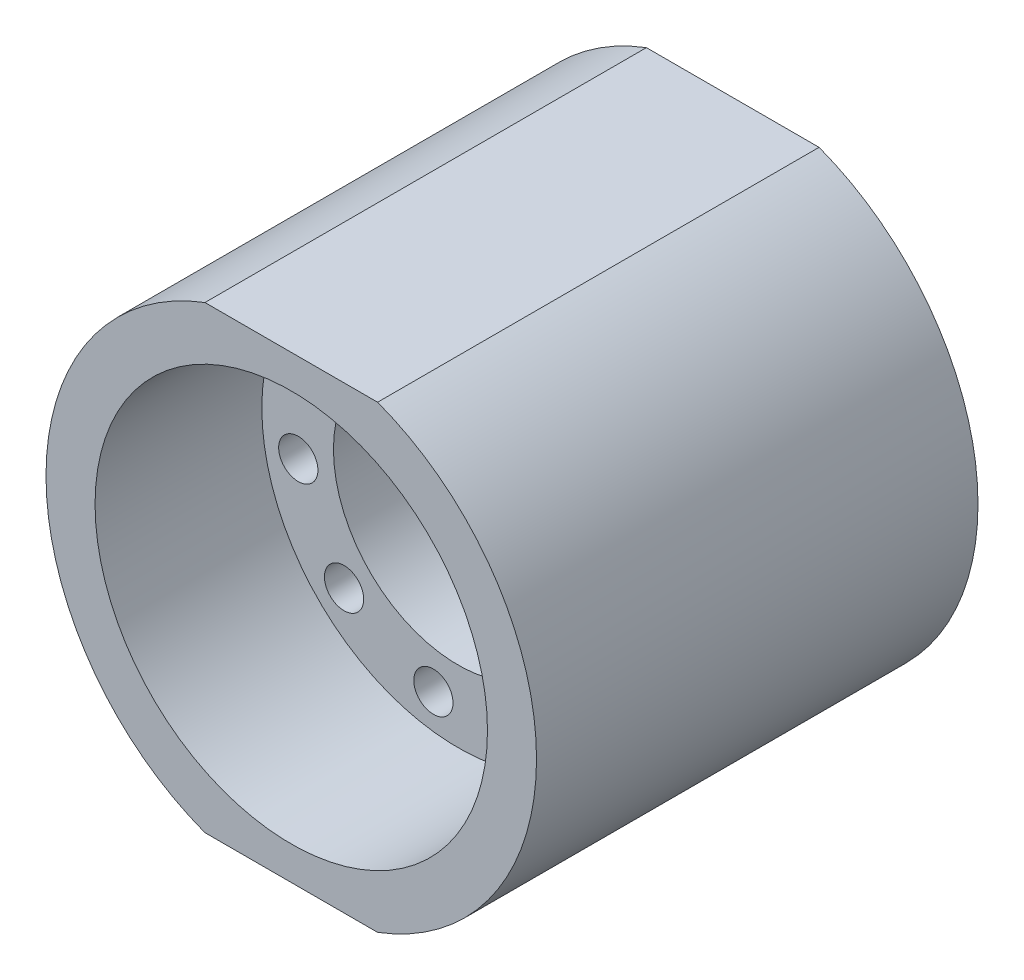
SolidWorks part; units mm, degrees
ref_plane "Front Plane" through (0, 0, 0) normal (0, 0, 1) x (1, 0, 0)
ref_plane "Top Plane" through (0, 0, 0) normal (0, 1, 0) x (1, 0, 0)
ref_plane "Right Plane" through (0, 0, 0) normal (1, 0, 0) x (0, 0, -1)
sketch "Sketch1" plane through (0, 0, 0) normal (0, 0, 1) x (1, 0, 0)
  circle A0 centre (0, 0) radius 25
  dimension "D1" = 50
extrude "Boss-Extrude1" add sketch "Sketch1" along normal blind 45
sketch "Sketch2" plane through (0, 0, 45) normal (0, 0, 1) x (1, 0, 0)
  circle A0 centre (0, 0) radius 20
  dimension "D1" = 40
extrude "Cut-Extrude1" cut sketch "Sketch2" against normal blind 17
sketch "Sketch3" plane through (0, 0, 28) normal (0, 0, 1) x (1, 0, 0)
  circle A0 centre (0, 0) radius 12.7
  dimension "D1" = 25.4
extrude "Cut-Extrude2" cut sketch "Sketch3" against normal blind 18
cosmetic thread "Cosmetic Thread1" parameters "D2"=28.575
sketch "Sketch4" plane through (0, 0, 28) normal (0, 0, 1) x (1, 0, 0)
  circle A0 centre (0, 0) radius 16.5 construction
  circle A1 centre (-7.5527, 14.6699) radius 2
  dimension "D1" = 33
  dimension "D2" = 4
extrude "Cut-Extrude3" cut sketch "Sketch4" against normal through all
pattern_circular "CirPattern1" count 10 over 360 about axis through (0, 0, 0) along (0, 0, 1) of "Cut-Extrude3"
sketch "Sketch5" plane through (0, 0, 0) normal (0, 0, -1) x (-1, 0, 0)
  circle A0 centre (0, 0) radius 20
  dimension "D1" = 40
extrude "Cut-Extrude4" cut sketch "Sketch5" against normal blind 20
cosmetic thread "Cosmetic Thread2" parameters "D1"=12, "D2"=44.45
sketch "Sketch6" plane through (0, 0, 0) normal (0, 0, -1) x (-1, 0, 0)
  line L0 (-8.8, 23.4) -> (8.8, 23.4)
  line L1 (-25, 0) -> (25, 0) construction
  line L2 (-8.8, -23.4) -> (8.8, -23.4)
  arc A1 (8.8, 23.4) -> (-8.8, 23.4) centre (0, 0) ccw
  circle A2 centre (0, 0) radius 25 construction
  arc A3 (8.8, -23.4) -> (-8.8, -23.4) centre (0, 0) cw
  dimension "D1" = 23.4
extrude "Cut-Extrude5" cut sketch "Sketch6" against normal through all
